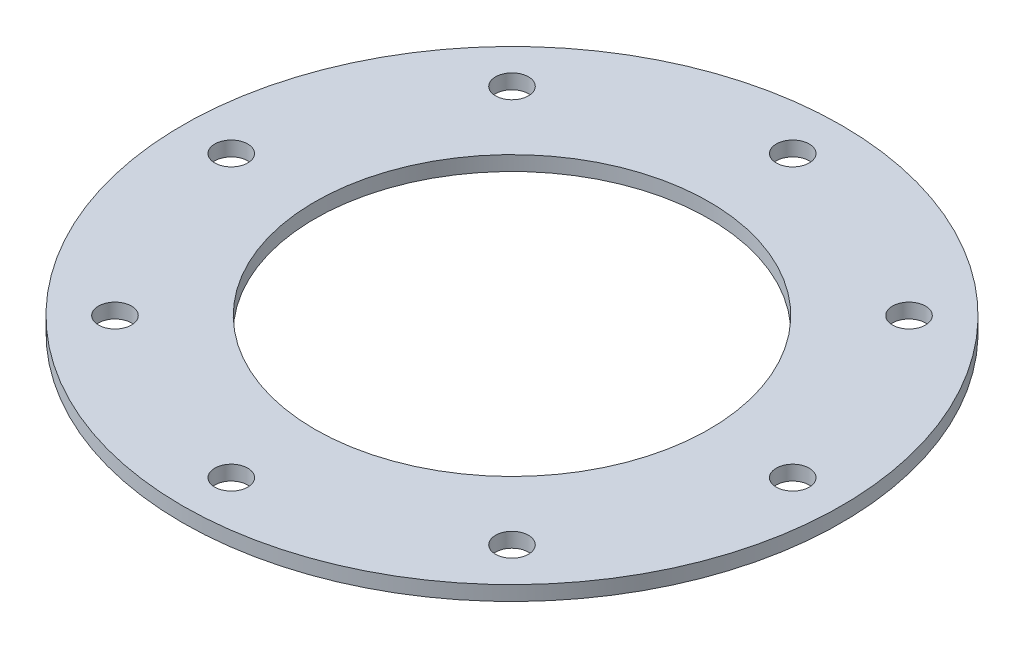
SolidWorks part; units mm, degrees
ref_plane "Front Plane" through (0, 0, 0) normal (0, 0, 1) x (1, 0, 0)
ref_plane "Top Plane" through (0, 0, 0) normal (0, 1, 0) x (1, 0, 0)
ref_plane "Right Plane" through (0, 0, 0) normal (1, 0, 0) x (0, 0, -1)
sketch "Sketch1" plane through (0, 0, 0) normal (0, 1, 0) x (1, 0, 0)
  circle A0 centre (0, 0) radius 135
  circle A1 centre (0, 0) radius 80.75
  circle A2 centre (0, 0) radius 75.75 construction
  dimension "D1" = 270
  dimension "D2" = 5
extrude "Boss-Extrude1" add sketch "Sketch1" along normal blind 6
sketch "Sketch2" plane through (0, 6, 0) normal (0, 1, 0) x (1, 0, 0)
  point P0 (0, 115)
  point P1 (81.3173, 81.3173)
  point P2 (115, 0)
  point P4 (81.3173, -81.3173)
  point P5 (0, -115)
  point P8 (-81.3173, -81.3173)
  point P9 (-115, 0)
  point P10 (-81.3173, 81.3173)
  point P11 (0, 0)
  dimension "D1" = 115
hole_wizard "M12 Clearance Hole1" positions "Sketch2" profile "Sketch3" hole size "M12" standard "ANSI Metric" end condition through all
sketch "Sketch3" plane through (0, 6, -115) normal (1, 0, 0) x (0, 0, 1)
  line L0 (0, 0) -> (0, 6)
  line L1 (0, 6) -> (6.75, 6)
  line L2 (6.75, 6) -> (6.75, 0)
  line L5 (6.75, 0) -> (0, 0)
  line L11 (0, -6.35) -> (0, 107.95) construction
  dimension "Thru Hole Dia." = 13.5
  dimension "Thru Hole Depth" = 6
